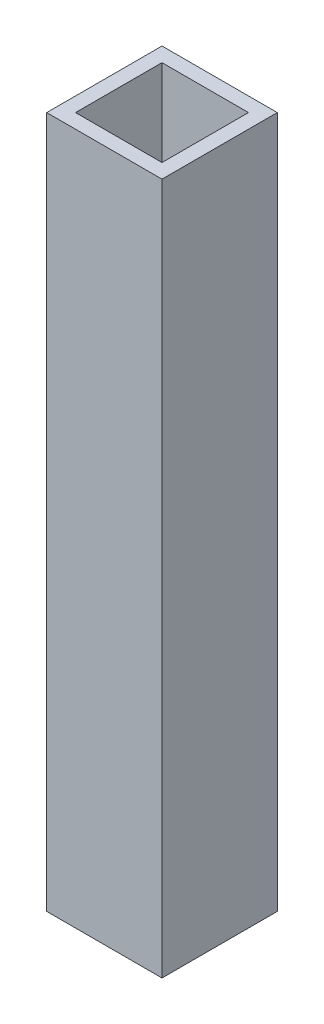
SolidWorks part; units mm, degrees
ref_plane "Front Plane" through (0, 0, 0) normal (0, 0, 1) x (1, 0, 0)
ref_plane "Top Plane" through (0, 0, 0) normal (0, 1, 0) x (1, 0, 0)
ref_plane "Right Plane" through (0, 0, 0) normal (1, 0, 0) x (0, 0, -1)
sketch "Sketch1" plane through (0, 0, 0) normal (0, 1, 0) x (1, 0, 0)
  line L1 (0, 0) -> (25.4, 0)
  line L2 (0, 0) -> (0, 25.4)
  line L3 (0, 25.4) -> (25.4, 25.4)
  line L4 (25.4, 0) -> (25.4, 25.4)
  line L5 (3.175, 3.175) -> (22.225, 3.175)
  line L6 (3.175, 3.175) -> (3.175, 22.225)
  line L7 (3.175, 22.225) -> (22.225, 22.225)
  line L8 (22.225, 3.175) -> (22.225, 22.225)
  dimension "D1" = 25.4
  dimension "D2" = 25.4
  dimension "D3" = 3.175
  dimension "D4" = 3.175
  dimension "D5" = 3.175
  dimension "D6" = 3.175
extrude "Boss-Extrude1" add sketch "Sketch1" along normal blind 152.4
